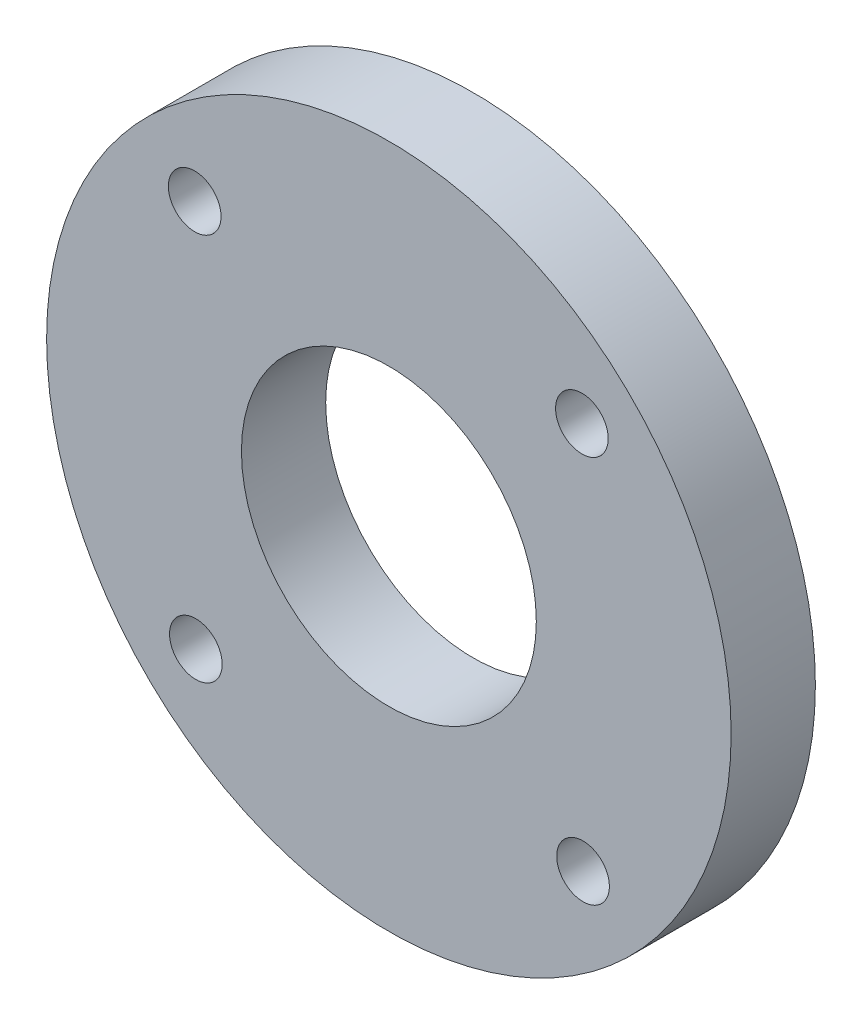
SolidWorks part; units mm, degrees
ref_plane "Спереди" through (0, 0, 0) normal (0, 0, 1) x (1, 0, 0)
ref_plane "Сверху" through (0, 0, 0) normal (0, 1, 0) x (1, 0, 0)
ref_plane "Справа" through (0, 0, 0) normal (1, 0, 0) x (0, 0, -1)
sketch "Эскиз2" plane through (0, 0, 0) normal (0, 0, 1) x (1, 0, 0)
  circle A0 centre (0, 0) radius 32.5
  circle A1 centre (-18.4388, 18.3277) radius 2.5
  circle A2 centre (-18.3277, -18.4388) radius 2.5
  circle A3 centre (18.3277, 18.4388) radius 2.5
  circle A4 centre (18.4388, -18.3277) radius 2.5
  circle A5 centre (0, 0) radius 14
  dimension "D1" = 5
  dimension "D2" = 28
  dimension "D3" = 5
  dimension "D4" = 5
  dimension "D5" = 5
  dimension "D6" = 65
  dimension "D7" = 18.4388
  dimension "D8" = 18.3277
  dimension "D9" = 18.4388
  dimension "D10" = 18.3277
  dimension "D11" = 18.3277
  dimension "D12" = 18.4388
  dimension "D13" = 18.3277
  dimension "D14" = 18.4388
extrude "Вытянуть2" add sketch "Эскиз2" along normal blind 8 separate body
